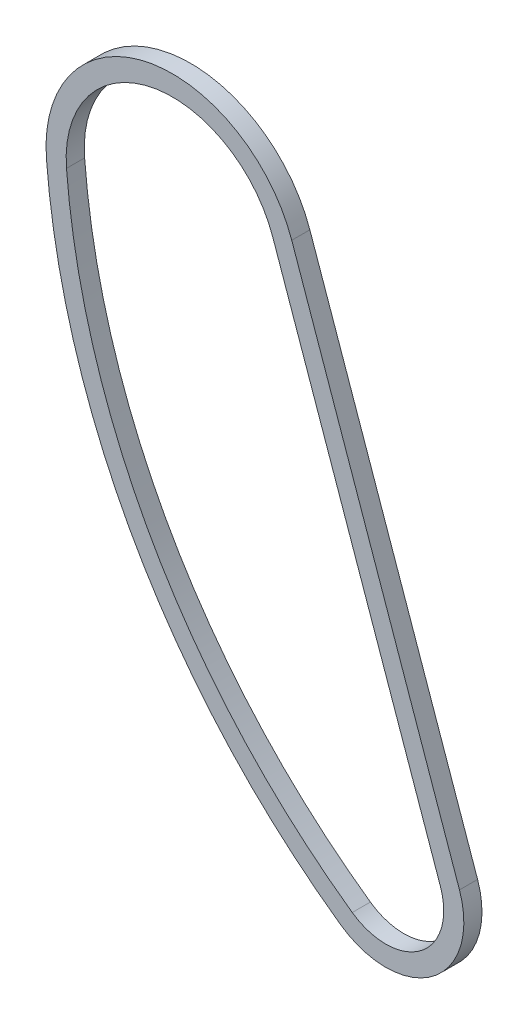
SolidWorks part; units mm, degrees
material "Plain Carbon Steel"
ref_plane "Front Plane" through (0, 0, 0) normal (0, 0, 1) x (1, 0, 0)
ref_plane "Top Plane" through (0, 0, 0) normal (0, 1, 0) x (1, 0, 0)
ref_plane "Right Plane" through (0, 0, 0) normal (1, 0, 0) x (0, 0, -1)
sketch "Sketch1" plane through (0, 0, 0) normal (0, 0, 1) x (1, 0, 0)
  line L0 (71.3182, -108.562) -> (29.6432, 10.3859)
  line L1 (66.5995, -110.2152) -> (24.9245, 8.7326)
  arc A0 (29.6432, 10.3859) -> (-31.3083, -2.5256) centre (0, 0) ccw
  arc A1 (-31.3083, -2.5256) -> (41.793, -130.8278) centre (142.4347, 11.4899) ccw
  arc A2 (41.793, -130.8278) -> (71.3182, -108.562) centre (53, -114.98) ccw
  arc A3 (24.9245, 8.7326) -> (-26.3245, -2.1235) centre (0, 0) ccw
  arc A4 (-26.3245, -2.1235) -> (44.6799, -126.7454) centre (142.4347, 11.4899) ccw
  arc A5 (44.6799, -126.7454) -> (66.5995, -110.2152) centre (53, -114.98) ccw
extrude "Boss-Extrude1" add sketch "Sketch1" along normal blind 4.5
